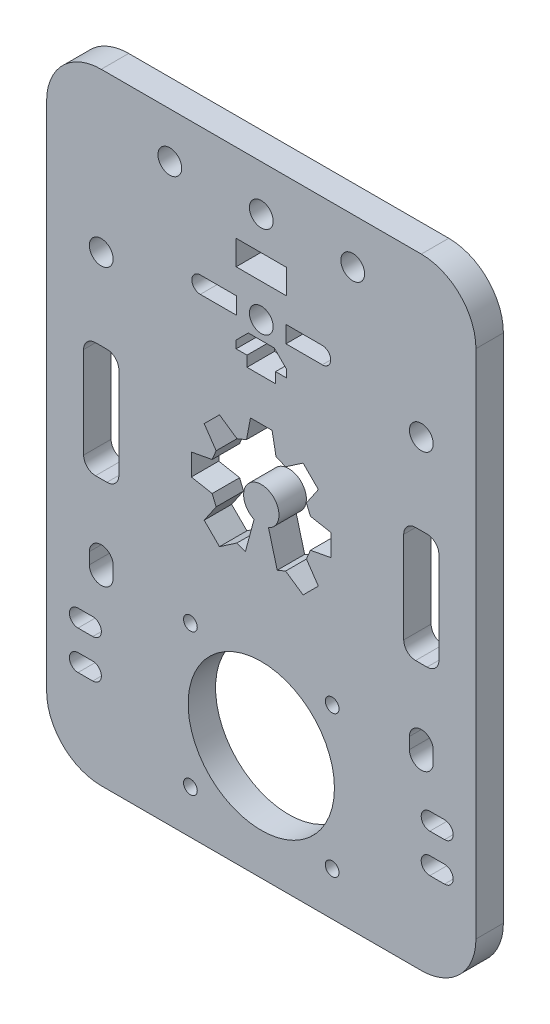
SolidWorks part; units mm, degrees
material "Acrílico (Impacto medio-alto)"
ref_plane "Alzado" through (0, 0, 0) normal (0, 0, 1) x (1, 0, 0)
ref_plane "Planta" through (0, 0, 0) normal (0, 1, 0) x (1, 0, 0)
ref_plane "Vista lateral" through (0, 0, 0) normal (1, 0, 0) x (0, 0, -1)
sketch "Croquis1" plane through (0, 0, 0) normal (0, 0, 1) x (1, 0, 0)
  line L0 (312.8597, 254.6486) -> (312.8597, 257.1486) construction
  line L1 (307.6597, 257.1486) -> (307.6597, 254.6486) construction
  line L2 (312.12, 241.4361) -> (315.3343, 241.4361) construction
  line L3 (315.3343, 245.2111) -> (312.12, 245.2111) construction
  line L4 (315.3343, 233.0113) -> (312.12, 233.0113) construction
  line L5 (312.12, 236.7863) -> (315.3343, 236.7863) construction
  line L6 (238.3995, 233.0113) -> (235.1851, 233.0113) construction
  line L7 (235.1851, 236.7863) -> (238.3995, 236.7863) construction
  line L8 (238.3995, 241.4361) -> (235.1851, 241.4361) construction
  line L9 (235.1851, 245.2111) -> (238.3995, 245.2111) construction
  line L10 (237.6597, 254.6486) -> (237.6597, 257.1486) construction
  line L11 (242.8597, 257.1486) -> (242.8597, 254.6486) construction
  line L12 (264.5175, 281.5753) -> (259.9661, 282.4368) construction
  line L13 (259.9661, 282.4368) -> (259.9661, 287.1605) construction
  line L14 (259.9661, 287.1605) -> (264.5175, 288.0219) construction
  line L15 (264.5175, 288.0219) -> (265.3846, 290.1153) construction
  line L16 (265.3846, 290.1153) -> (262.7754, 293.9427) construction
  line L17 (262.7754, 293.9427) -> (266.1156, 297.2829) construction
  line L18 (266.1156, 297.2829) -> (269.943, 294.6737) construction
  line L19 (269.943, 294.6737) -> (272.0364, 295.5408) construction
  line L20 (272.0364, 295.5408) -> (272.8979, 300.0922) construction
  line L21 (272.8979, 300.0922) -> (277.6216, 300.0922) construction
  line L22 (277.6216, 300.0922) -> (278.483, 295.5408) construction
  line L23 (278.483, 295.5408) -> (280.5764, 294.6737) construction
  line L24 (280.5764, 294.6737) -> (284.4038, 297.2829) construction
  line L25 (284.4038, 297.2829) -> (287.744, 293.9427) construction
  line L26 (287.744, 293.9427) -> (285.1348, 290.1153) construction
  line L27 (285.1348, 290.1153) -> (286.0019, 288.0219) construction
  line L28 (286.0019, 288.0219) -> (290.5533, 287.1605) construction
  line L29 (290.5533, 287.1605) -> (290.5533, 282.4368) construction
  line L30 (290.5533, 282.4368) -> (286.0019, 281.5753) construction
  line L31 (286.0019, 281.5753) -> (285.1348, 279.4819) construction
  line L32 (285.1348, 279.4819) -> (287.744, 275.6545) construction
  line L33 (287.744, 275.6545) -> (284.4038, 272.3143) construction
  line L34 (284.4038, 272.3143) -> (280.5764, 274.9235) construction
  line L35 (280.5764, 274.9235) -> (278.7437, 274.1644) construction
  line L36 (278.7437, 274.1644) -> (276.8403, 281.268) construction
  line L37 (273.6791, 281.268) -> (271.7757, 274.1644) construction
  line L38 (271.7757, 274.1644) -> (269.943, 274.9235) construction
  line L39 (269.943, 274.9235) -> (266.1156, 272.3143) construction
  line L40 (266.1156, 272.3143) -> (262.7754, 275.6545) construction
  line L41 (262.7754, 275.6545) -> (265.3846, 279.4819) construction
  line L42 (265.3846, 279.4819) -> (264.5175, 281.5753) construction
  line L43 (244.1097, 274.7986) -> (244.1097, 294.7986) construction
  line L44 (241.5097, 297.3986) -> (239.0097, 297.3986) construction
  line L45 (236.4097, 294.7986) -> (236.4097, 274.7986) construction
  line L46 (239.0097, 272.1986) -> (241.5097, 272.1986) construction
  line L47 (314.1097, 294.7986) -> (314.1097, 274.7986) construction
  line L48 (311.5097, 272.1986) -> (309.0097, 272.1986) construction
  line L49 (306.4097, 274.7986) -> (306.4097, 294.7986) construction
  line L50 (309.0097, 297.3986) -> (311.5097, 297.3986) construction
  line L51 (272.1347, 309.2941) -> (278.3847, 309.2941) construction
  line L52 (278.3847, 309.2941) -> (278.3847, 311.5986) construction
  line L53 (278.3847, 311.5986) -> (280.7597, 311.5986) construction
  line L54 (280.7597, 311.5986) -> (280.7597, 313.2784) construction
  line L55 (280.7597, 313.2784) -> (278.099, 315.9391) construction
  line L56 (278.099, 315.9391) -> (272.4204, 315.9391) construction
  line L57 (272.4204, 315.9391) -> (269.7597, 313.2784) construction
  line L58 (269.7597, 313.2784) -> (269.7597, 311.5986) construction
  line L59 (269.7597, 311.5986) -> (272.1347, 311.5986) construction
  line L60 (272.1347, 311.5986) -> (272.1347, 309.2941) construction
  line L61 (269.8597, 318.0016) -> (261.9193, 318.0016) construction
  line L62 (269.8597, 321.6766) -> (261.9193, 321.6766) construction
  line L63 (269.8597, 321.6766) -> (269.8597, 318.0016) construction
  line L64 (288.6001, 321.6766) -> (280.6597, 321.6766) construction
  line L65 (280.6597, 321.6766) -> (280.6597, 318.0016) construction
  line L66 (280.6597, 318.0016) -> (288.6001, 318.0016) construction
  line L67 (280.7597, 332.5391) -> (280.7597, 327.1391) construction
  line L68 (269.7597, 327.1391) -> (280.7597, 327.1391) construction
  line L69 (269.7597, 332.5391) -> (269.7597, 327.1391) construction
  line L70 (269.7597, 332.5391) -> (280.7597, 332.5391) construction
  line L71 (240.2597, 349.7986) -> (310.2597, 349.7986) construction
  line L72 (322.2047, 337.8536) -> (322.2047, 226.0436) construction
  line L73 (310.2597, 214.0986) -> (240.2597, 214.0986) construction
  line L74 (228.3147, 226.0436) -> (228.3147, 337.8536) construction
  line L75 (312.8597, 254.6486) -> (312.8597, 257.1486)
  line L76 (307.6597, 257.1486) -> (307.6597, 254.6486)
  line L77 (312.12, 241.4361) -> (315.3343, 241.4361)
  line L78 (315.3343, 245.2111) -> (312.12, 245.2111)
  line L79 (315.3343, 233.0113) -> (312.12, 233.0113)
  line L80 (312.12, 236.7863) -> (315.3343, 236.7863)
  line L81 (238.3995, 233.0113) -> (235.1851, 233.0113)
  line L82 (235.1851, 236.7863) -> (238.3995, 236.7863)
  line L83 (238.3995, 241.4361) -> (235.1851, 241.4361)
  line L84 (235.1851, 245.2111) -> (238.3995, 245.2111)
  line L85 (237.6597, 254.6486) -> (237.6597, 257.1486)
  line L86 (242.8597, 257.1486) -> (242.8597, 254.6486)
  line L87 (264.5175, 281.5753) -> (259.9661, 282.4368)
  line L88 (259.9661, 282.4368) -> (259.9661, 287.1605)
  line L89 (259.9661, 287.1605) -> (264.5175, 288.0219)
  line L90 (264.5175, 288.0219) -> (265.3846, 290.1153)
  line L91 (265.3846, 290.1153) -> (262.7754, 293.9427)
  line L92 (262.7754, 293.9427) -> (266.1156, 297.2829)
  line L93 (266.1156, 297.2829) -> (269.943, 294.6737)
  line L94 (269.943, 294.6737) -> (272.0364, 295.5408)
  line L95 (272.0364, 295.5408) -> (272.8979, 300.0922)
  line L96 (272.8979, 300.0922) -> (277.6216, 300.0922)
  line L97 (277.6216, 300.0922) -> (278.483, 295.5408)
  line L98 (278.483, 295.5408) -> (280.5764, 294.6737)
  line L99 (280.5764, 294.6737) -> (284.4038, 297.2829)
  line L100 (284.4038, 297.2829) -> (287.744, 293.9427)
  line L101 (287.744, 293.9427) -> (285.1348, 290.1153)
  line L102 (285.1348, 290.1153) -> (286.0019, 288.0219)
  line L103 (286.0019, 288.0219) -> (290.5533, 287.1605)
  line L104 (290.5533, 287.1605) -> (290.5533, 282.4368)
  line L105 (290.5533, 282.4368) -> (286.0019, 281.5753)
  line L106 (286.0019, 281.5753) -> (285.1348, 279.4819)
  line L107 (285.1348, 279.4819) -> (287.744, 275.6545)
  line L108 (287.744, 275.6545) -> (284.4038, 272.3143)
  line L109 (284.4038, 272.3143) -> (280.5764, 274.9235)
  line L110 (280.5764, 274.9235) -> (278.7437, 274.1644)
  line L111 (278.7437, 274.1644) -> (276.8403, 281.268)
  line L112 (273.6791, 281.268) -> (271.7757, 274.1644)
  line L113 (271.7757, 274.1644) -> (269.943, 274.9235)
  line L114 (269.943, 274.9235) -> (266.1156, 272.3143)
  line L115 (266.1156, 272.3143) -> (262.7754, 275.6545)
  line L116 (262.7754, 275.6545) -> (265.3846, 279.4819)
  line L117 (265.3846, 279.4819) -> (264.5175, 281.5753)
  line L118 (244.1097, 274.7986) -> (244.1097, 294.7986)
  line L119 (241.5097, 297.3986) -> (239.0097, 297.3986)
  line L120 (236.4097, 294.7986) -> (236.4097, 274.7986)
  line L121 (239.0097, 272.1986) -> (241.5097, 272.1986)
  line L122 (314.1097, 294.7986) -> (314.1097, 274.7986)
  line L123 (311.5097, 272.1986) -> (309.0097, 272.1986)
  line L124 (306.4097, 274.7986) -> (306.4097, 294.7986)
  line L125 (309.0097, 297.3986) -> (311.5097, 297.3986)
  line L126 (272.1347, 309.2941) -> (278.3847, 309.2941)
  line L127 (278.3847, 309.2941) -> (278.3847, 311.5986)
  line L128 (278.3847, 311.5986) -> (280.7597, 311.5986)
  line L129 (280.7597, 311.5986) -> (280.7597, 313.2784)
  line L130 (280.7597, 313.2784) -> (278.099, 315.9391)
  line L131 (278.099, 315.9391) -> (272.4204, 315.9391)
  line L132 (272.4204, 315.9391) -> (269.7597, 313.2784)
  line L133 (269.7597, 313.2784) -> (269.7597, 311.5986)
  line L134 (269.7597, 311.5986) -> (272.1347, 311.5986)
  line L135 (272.1347, 311.5986) -> (272.1347, 309.2941)
  line L136 (269.8597, 318.0016) -> (261.9193, 318.0016)
  line L137 (269.8597, 321.6766) -> (261.9193, 321.6766)
  line L138 (269.8597, 321.6766) -> (269.8597, 318.0016)
  line L139 (288.6001, 321.6766) -> (280.6597, 321.6766)
  line L140 (280.6597, 321.6766) -> (280.6597, 318.0016)
  line L141 (280.6597, 318.0016) -> (288.6001, 318.0016)
  line L142 (280.7597, 332.5391) -> (280.7597, 327.1391)
  line L143 (269.7597, 327.1391) -> (280.7597, 327.1391)
  line L144 (269.7597, 332.5391) -> (269.7597, 327.1391)
  line L145 (269.7597, 332.5391) -> (280.7597, 332.5391)
  line L146 (240.2597, 349.7986) -> (310.2597, 349.7986)
  line L147 (322.2047, 337.8536) -> (322.2047, 226.0436)
  line L148 (310.2597, 214.0986) -> (240.2597, 214.0986)
  line L149 (228.3147, 226.0436) -> (228.3147, 337.8536)
  arc A0 (307.6597, 254.6486) -> (312.8597, 254.6486) centre (310.2597, 254.6486) ccw construction
  arc A1 (312.8597, 257.1486) -> (307.6597, 257.1486) centre (310.2597, 257.1486) ccw construction
  arc A2 (315.3343, 241.4361) -> (315.3343, 245.2111) centre (315.3343, 243.3236) ccw construction
  arc A3 (312.12, 245.2111) -> (312.12, 241.4361) centre (312.12, 243.3236) ccw construction
  arc A4 (312.12, 236.7863) -> (312.12, 233.0113) centre (312.12, 234.8988) ccw construction
  arc A5 (315.3343, 233.0113) -> (315.3343, 236.7863) centre (315.3343, 234.8988) ccw construction
  circle A6 centre (259.7597, 223.6486) radius 1.5 construction
  circle A7 centre (290.7597, 223.6486) radius 1.5 construction
  circle A8 centre (290.7597, 254.6486) radius 1.5 construction
  circle A9 centre (259.7597, 254.6486) radius 1.5 construction
  circle A10 centre (275.2597, 239.1486) radius 16 construction
  arc A11 (238.3995, 233.0113) -> (238.3995, 236.7863) centre (238.3995, 234.8988) ccw construction
  arc A12 (235.1851, 236.7863) -> (235.1851, 233.0113) centre (235.1851, 234.8988) ccw construction
  arc A13 (238.3995, 241.4361) -> (238.3995, 245.2111) centre (238.3995, 243.3236) ccw construction
  arc A14 (235.1851, 245.2111) -> (235.1851, 241.4361) centre (235.1851, 243.3236) ccw construction
  arc A15 (237.6597, 254.6486) -> (242.8597, 254.6486) centre (240.2597, 254.6486) ccw construction
  arc A16 (242.8597, 257.1486) -> (237.6597, 257.1486) centre (240.2597, 257.1486) ccw construction
  arc A17 (276.8403, 281.268) -> (273.6791, 281.268) centre (275.2597, 284.7986) ccw construction
  arc A18 (244.1097, 294.7986) -> (241.5097, 297.3986) centre (241.5097, 294.7986) ccw construction
  arc A19 (239.0097, 297.3986) -> (236.4097, 294.7986) centre (239.0097, 294.7986) ccw construction
  arc A20 (236.4097, 274.7986) -> (239.0097, 272.1986) centre (239.0097, 274.7986) ccw construction
  arc A21 (241.5097, 272.1986) -> (244.1097, 274.7986) centre (241.5097, 274.7986) ccw construction
  arc A22 (311.5097, 272.1986) -> (314.1097, 274.7986) centre (311.5097, 274.7986) ccw construction
  arc A23 (306.4097, 274.7986) -> (309.0097, 272.1986) centre (309.0097, 274.7986) ccw construction
  arc A24 (309.0097, 297.3986) -> (306.4097, 294.7986) centre (309.0097, 294.7986) ccw construction
  arc A25 (314.1097, 294.7986) -> (311.5097, 297.3986) centre (311.5097, 294.7986) ccw construction
  circle A26 centre (310.2597, 315.1486) radius 2.6 construction
  circle A27 centre (240.2597, 315.1486) radius 2.6 construction
  arc A28 (261.9193, 321.6766) -> (261.9193, 318.0016) centre (261.9193, 319.8391) ccw construction
  circle A29 centre (275.2597, 319.8391) radius 2.6 construction
  arc A30 (288.6001, 318.0016) -> (288.6001, 321.6766) centre (288.6001, 319.8391) ccw construction
  circle A31 centre (295.2597, 339.8391) radius 2.6 construction
  circle A32 centre (275.2597, 339.8391) radius 2.6 construction
  circle A33 centre (255.2597, 339.8391) radius 2.6 construction
  arc A34 (240.2597, 349.7986) -> (228.3147, 337.8536) centre (240.2597, 337.8536) ccw construction
  arc A35 (322.2047, 337.8536) -> (310.2597, 349.7986) centre (310.2597, 337.8536) ccw construction
  arc A36 (310.2597, 214.0986) -> (322.2047, 226.0436) centre (310.2597, 226.0436) ccw construction
  arc A37 (228.3147, 226.0436) -> (240.2597, 214.0986) centre (240.2597, 226.0436) ccw construction
  arc A38 (307.6597, 254.6486) -> (312.8597, 254.6486) centre (310.2597, 254.6486) ccw
  arc A39 (312.8597, 257.1486) -> (307.6597, 257.1486) centre (310.2597, 257.1486) ccw
  arc A40 (315.3343, 241.4361) -> (315.3343, 245.2111) centre (315.3343, 243.3236) ccw
  arc A41 (312.12, 245.2111) -> (312.12, 241.4361) centre (312.12, 243.3236) ccw
  arc A42 (312.12, 236.7863) -> (312.12, 233.0113) centre (312.12, 234.8988) ccw
  arc A43 (315.3343, 233.0113) -> (315.3343, 236.7863) centre (315.3343, 234.8988) ccw
  circle A44 centre (259.7597, 223.6486) radius 1.5
  circle A45 centre (290.7597, 223.6486) radius 1.5
  circle A46 centre (290.7597, 254.6486) radius 1.5
  circle A47 centre (259.7597, 254.6486) radius 1.5
  circle A48 centre (275.2597, 239.1486) radius 16
  arc A49 (238.3995, 233.0113) -> (238.3995, 236.7863) centre (238.3995, 234.8988) ccw
  arc A50 (235.1851, 236.7863) -> (235.1851, 233.0113) centre (235.1851, 234.8988) ccw
  arc A51 (238.3995, 241.4361) -> (238.3995, 245.2111) centre (238.3995, 243.3236) ccw
  arc A52 (235.1851, 245.2111) -> (235.1851, 241.4361) centre (235.1851, 243.3236) ccw
  arc A53 (237.6597, 254.6486) -> (242.8597, 254.6486) centre (240.2597, 254.6486) ccw
  arc A54 (242.8597, 257.1486) -> (237.6597, 257.1486) centre (240.2597, 257.1486) ccw
  arc A55 (276.8403, 281.268) -> (273.6791, 281.268) centre (275.2597, 284.7986) ccw
  arc A56 (244.1097, 294.7986) -> (241.5097, 297.3986) centre (241.5097, 294.7986) ccw
  arc A57 (239.0097, 297.3986) -> (236.4097, 294.7986) centre (239.0097, 294.7986) ccw
  arc A58 (236.4097, 274.7986) -> (239.0097, 272.1986) centre (239.0097, 274.7986) ccw
  arc A59 (241.5097, 272.1986) -> (244.1097, 274.7986) centre (241.5097, 274.7986) ccw
  arc A60 (311.5097, 272.1986) -> (314.1097, 274.7986) centre (311.5097, 274.7986) ccw
  arc A61 (306.4097, 274.7986) -> (309.0097, 272.1986) centre (309.0097, 274.7986) ccw
  arc A62 (309.0097, 297.3986) -> (306.4097, 294.7986) centre (309.0097, 294.7986) ccw
  arc A63 (314.1097, 294.7986) -> (311.5097, 297.3986) centre (311.5097, 294.7986) ccw
  circle A64 centre (310.2597, 315.1486) radius 2.6
  circle A65 centre (240.2597, 315.1486) radius 2.6
  arc A66 (261.9193, 321.6766) -> (261.9193, 318.0016) centre (261.9193, 319.8391) ccw
  circle A67 centre (275.2597, 319.8391) radius 2.6
  arc A68 (288.6001, 318.0016) -> (288.6001, 321.6766) centre (288.6001, 319.8391) ccw
  circle A69 centre (295.2597, 339.8391) radius 2.6
  circle A70 centre (275.2597, 339.8391) radius 2.6
  circle A71 centre (255.2597, 339.8391) radius 2.6
  arc A72 (240.2597, 349.7986) -> (228.3147, 337.8536) centre (240.2597, 337.8536) ccw
  arc A73 (322.2047, 337.8536) -> (310.2597, 349.7986) centre (310.2597, 337.8536) ccw
  arc A74 (310.2597, 214.0986) -> (322.2047, 226.0436) centre (310.2597, 226.0436) ccw
  arc A75 (228.3147, 226.0436) -> (240.2597, 214.0986) centre (240.2597, 226.0436) ccw
extrude "Saliente-Extruir1" add sketch "Croquis1" along normal blind 6
